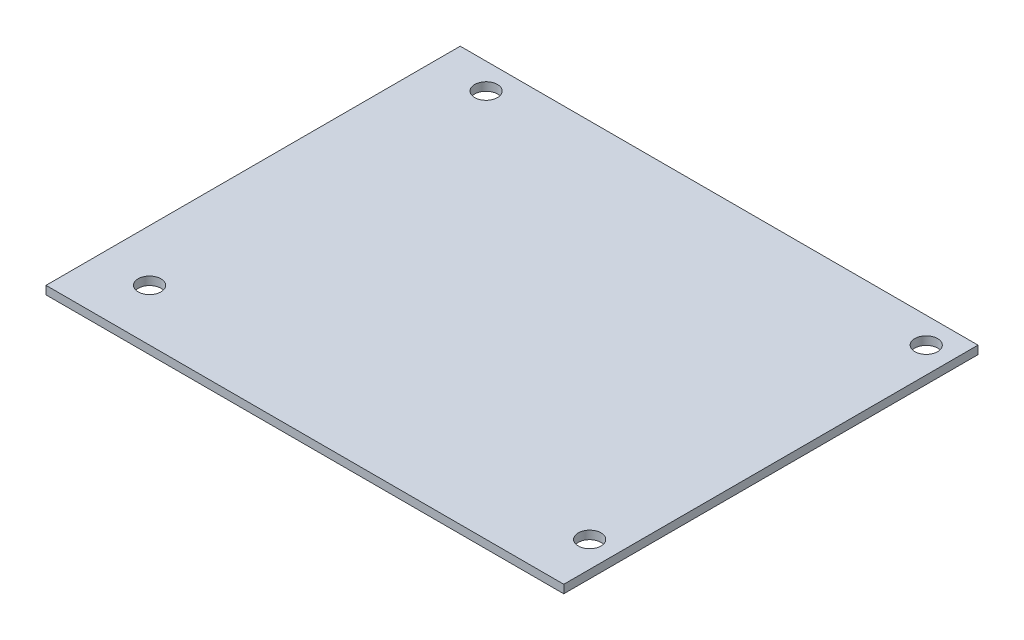
SolidWorks part; units mm, degrees
ref_plane "Front Plane" through (0, 0, 0) normal (0, 0, 1) x (1, 0, 0)
ref_plane "Top Plane" through (0, 0, 0) normal (0, 1, 0) x (1, 0, 0)
ref_plane "Right Plane" through (0, 0, 0) normal (1, 0, 0) x (0, 0, -1)
sketch "Sketch1" plane through (0, 0, 0) normal (0, 1, 0) x (1, 0, 0)
  line L1 (-50, 40) -> (50, 40)
  line L2 (-50, 40) -> (-50, -40)
  line L3 (-50, -40) -> (50, -40)
  line L4 (50, 40) -> (50, -40)
  line L5 (-50, 40) -> (50, -40) construction
  line L6 (-50, -40) -> (50, 40) construction
  point P0 (0, 0)
  dimension "D1" = 80
  dimension "D2" = 100
extrude "Boss-Extrude1" add sketch "Sketch1" along normal blind 1.6
sketch "Sketch2" plane through (0, 1.6, 0) normal (0, 1, 0) x (1, 0, 0)
  line L0 (-50, 40) -> (-50, -40) construction
  line L1 (-50, -40) -> (50, -40) construction
  circle A0 centre (-40, -30) radius 2.2
  circle A1 centre (-40, 35) radius 2.2
  circle A2 centre (45, 35) radius 2.2
  circle A3 centre (45, -30) radius 2.2
  dimension "D1" = 4.4
  dimension "D2" = 10
  dimension "D3" = 95
  dimension "D4" = 75
  dimension "D5" = 10
extrude "Cut-Extrude1" cut sketch "Sketch2" against normal through all
